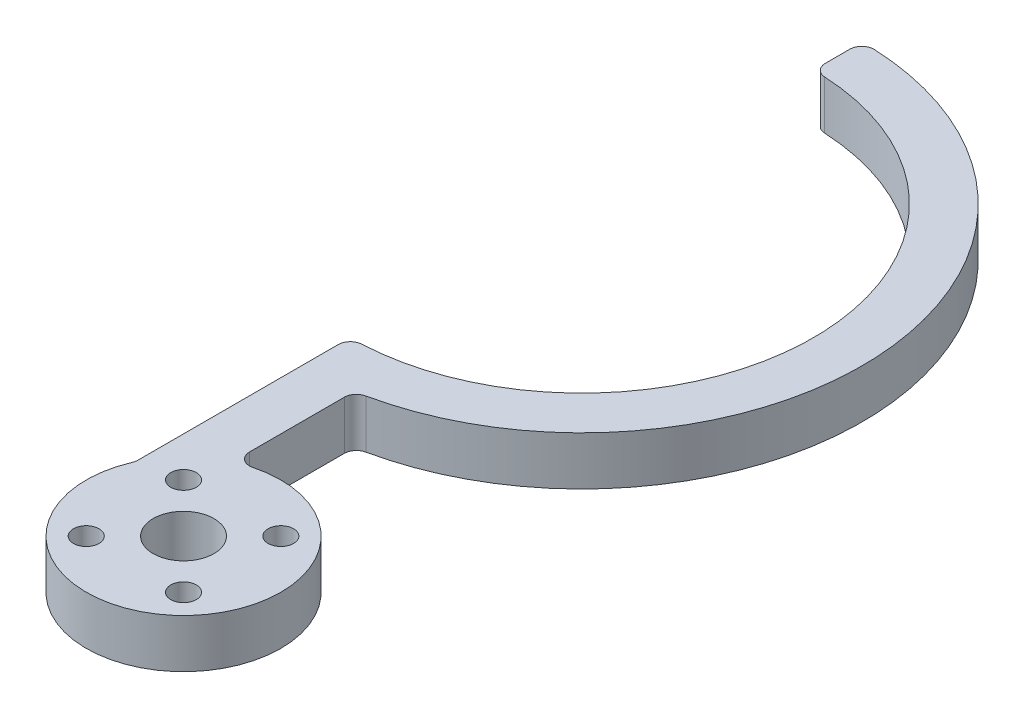
SolidWorks part; units mm, degrees
ref_plane "Front Plane" through (0, 0, 0) normal (0, 0, 1) x (1, 0, 0)
ref_plane "Top Plane" through (0, 0, 0) normal (0, 1, 0) x (1, 0, 0)
ref_plane "Right Plane" through (0, 0, 0) normal (1, 0, 0) x (0, 0, -1)
sketch "Sketch1" plane through (0, 0, 0) normal (0, 1, 0) x (1, 0, 0)
  line L0 (0, 46.1) -> (0, 38.1)
  line L3 (8, -45.4006) -> (8, -65.4413)
  line L7 (0, -38.1) -> (0, -73.4006)
  line L14 (8, -73.4006) -> (0, -73.4006) construction
  line L15 (0, -73.4006) -> (8, -65.4413) construction
  line L16 (6.5598, -72.0348) -> (22.5598, -72.0348) construction
  line L17 (6.5598, -72.0348) -> (6.5598, -88.0348) construction
  line L18 (6.5598, -88.0348) -> (22.5598, -88.0348) construction
  line L19 (22.5598, -72.0348) -> (22.5598, -88.0348) construction
  line L20 (6.5598, -72.0348) -> (22.5598, -88.0348) construction
  line L23 (6.5598, -88.0348) -> (22.5598, -72.0348) construction
  arc A0 (0, -38.1) -> (0, 38.1) centre (0, 0) ccw
  arc A1 (8, -45.4006) -> (0, 46.1) centre (0, 0) ccw
  arc A13 (0, -73.4006) -> (8, -65.4413) centre (14.5598, -80.0348) ccw
  circle A14 centre (22.5598, -72.0348) radius 2.1
  circle A15 centre (22.5598, -88.0348) radius 2.1
  circle A16 centre (6.5598, -88.0348) radius 2.1
  circle A17 centre (6.5598, -72.0348) radius 2.1
  circle A18 centre (14.5598, -80.0348) radius 5
  dimension "D1" = 76.2
  dimension "D4" = 16
  dimension "D7" = 4.2
  dimension "D8" = 10
  dimension "D2" = 8
  dimension "D5" = 28
  dimension "D3" = 8
  dimension "D6" = 16
extrude "Boss-Extrude2" add sketch "Sketch1" along normal blind 8
fillet "Fillet1" radius 2 6 edges at (0, 4, -38.1) (0, 4, -46.1) (8, 4, 45.4006) (8, 4, 65.4413) (0, 4, 73.4006) (0, 4, 38.1)
equation "\"innerSmall\" = 3in"
equation "\"thick\"= 8mm"
equation "\"D1@Sketch1\"=\"innerSmall\""
equation "\"D2@Sketch1\"=\"thick\""
equation "\"D3@Sketch1\"=\"thick\""
